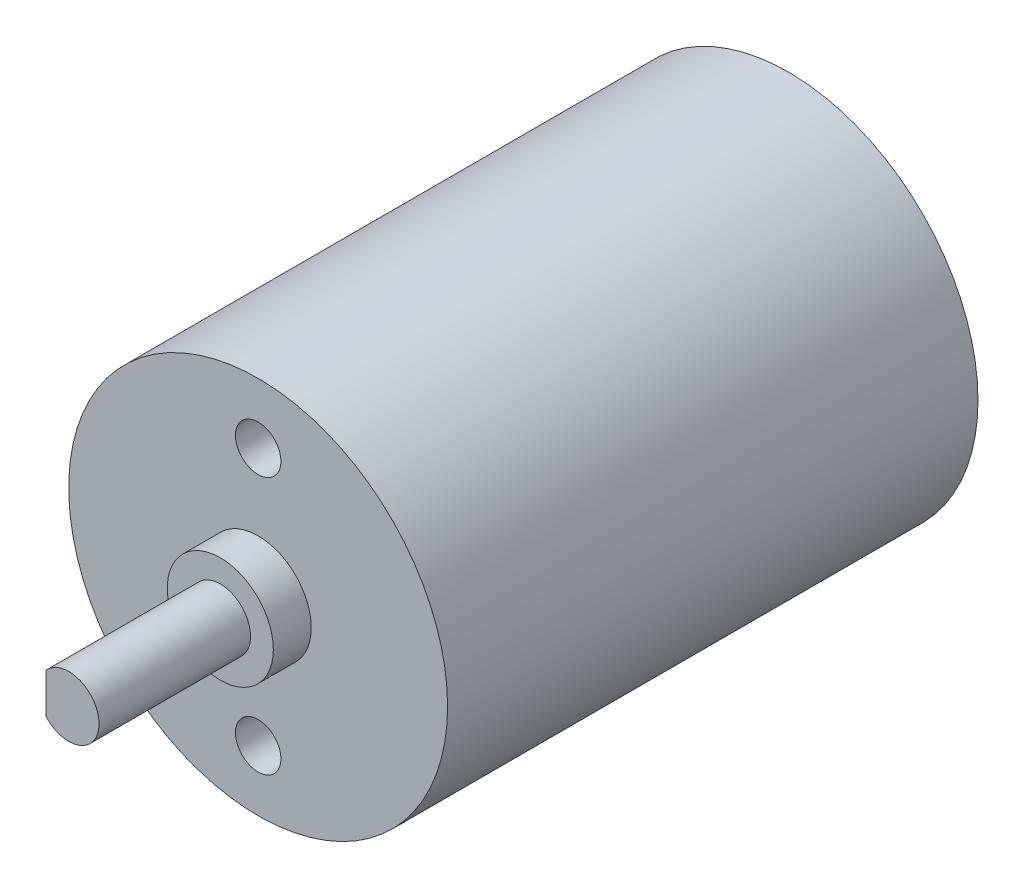
SolidWorks part; units mm, degrees
ref_plane "前视基准面" through (0, 0, 0) normal (0, 0, 1) x (1, 0, 0)
ref_plane "上视基准面" through (0, 0, 0) normal (0, 1, 0) x (1, 0, 0)
ref_plane "右视基准面" through (0, 0, 0) normal (1, 0, 0) x (0, 0, -1)
other "Configuration Table"
sketch "草图1" plane through (0, 0, 0) normal (0, 0, 1) x (1, 0, 0)
  circle A0 centre (0, 0) radius 12.5
  dimension "D1" = 25
extrude "凸台-拉伸1" add sketch "草图1" along normal blind 35
sketch "草图2" plane through (0, 0, 35) normal (0, 0, 1) x (1, 0, 0)
  circle A0 centre (0, 0) radius 3.5
  dimension "D1" = 7
extrude "凸台-拉伸2" add sketch "草图2" along normal blind 2.5
sketch "草图3" plane through (0, 0, 37.5) normal (0, 0, 1) x (1, 0, 0)
  circle A0 centre (0, 0) radius 2
  dimension "D1" = 4
extrude "凸台-拉伸3" add sketch "草图3" along normal blind 10
sketch "草图4" plane through (0, 0, 47.5) normal (0, 0, 1) x (1, 0, 0)
  line L0 (-1.5, 1.3229) -> (-1.5, -1.3229)
  arc A0 (-1.5, 1.3229) -> (-1.5, -1.3229) centre (0, 0) ccw
  dimension "D2" = 4
  dimension "D1" = 1.5
extrude "切除-拉伸1" cut sketch "草图4" against normal up to surface (10 mm away) up to face at (2, 0, 37.5)
sketch "草图5" plane through (0, 0, 35) normal (0, 0, 1) x (1, 0, 0)
  circle A1 centre (0, 8.5) radius 1.5
  circle A2 centre (0, -8.5) radius 1.5
  point P10 (0, 0)
  dimension "D1" = 8.5
  dimension "D2" = 3
  dimension "D3" = 2
extrude "切除-拉伸2" cut sketch "草图5" against normal blind 4.5
